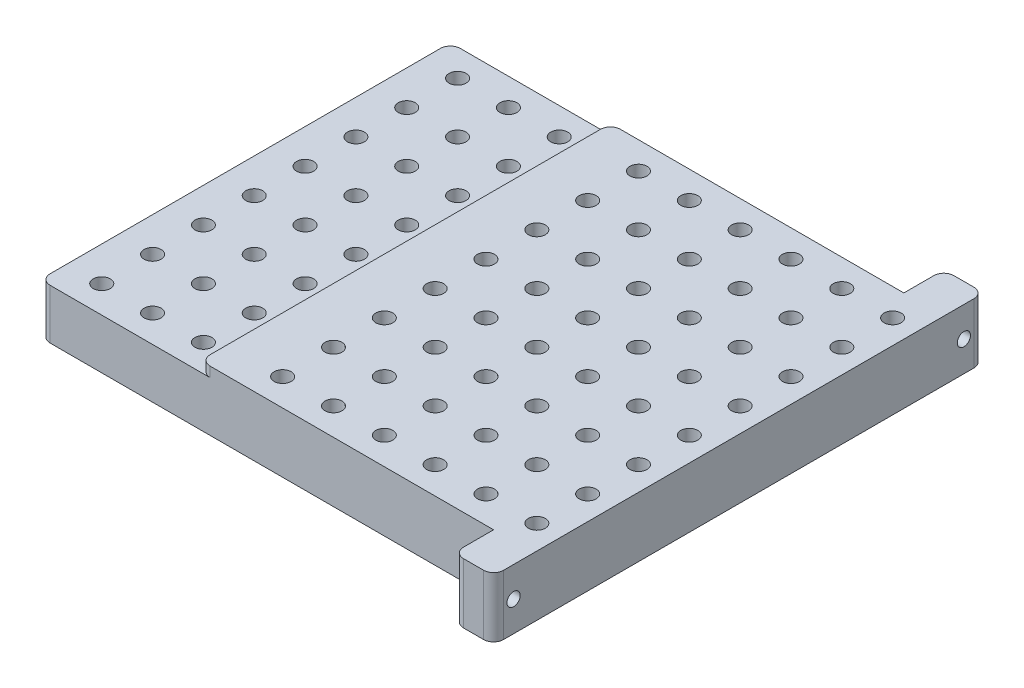
SolidWorks part; units mm, degrees
ref_plane "Front Plane" through (0, 0, 0) normal (0, 0, 1) x (1, 0, 0)
ref_plane "Top Plane" through (0, 0, 0) normal (0, 1, 0) x (1, 0, 0)
ref_plane "Right Plane" through (0, 0, 0) normal (1, 0, 0) x (0, 0, -1)
sketch "Sketch1" plane through (0, 0, 0) normal (0, 0, 1) x (1, 0, 0)
  line L0 (-80, 0) -> (0, 0)
  line L1 (0, 0) -> (0, 5)
  line L2 (0, 5) -> (166.6, 5)
  line L3 (166.6, 5) -> (166.6, -25)
  line L4 (166.6, -25) -> (-80, -25)
  line L5 (-80, -25) -> (-80, 0)
  dimension "D1" = 5
  dimension "D2" = 80
  dimension "D3" = 166.6
  dimension "D4" = 25
extrude "Boss-Extrude1" add sketch "Sketch1" along normal blind 205
sketch "Sketch2" plane through (0, 5, 0) normal (0, 1, 0) x (1, 0, 0)
  line L0 (0, -205) -> (0, 0) construction
  line L2 (166.6, 0) -> (0, 0) construction
  line L4 (166.6, -205) -> (0, -205) construction
  line L7 (-80, -39) -> (166.6, -39) construction
  line L8 (-80, -205) -> (-80, 0) construction
  line L9 (166.6, -205) -> (166.6, 0) construction
  line L11 (-80, -89.8) -> (166.6, -89.8) construction
  line L13 (-80, -140.6) -> (166.6, -140.6) construction
  line L15 (-80, -191.4) -> (166.6, -191.4) construction
  line L17 (-62.8, 0) -> (-62.8, -205) construction
  line L18 (0, 0) -> (-80, 0) construction
  line L19 (0, -205) -> (-80, -205) construction
  line L21 (-12, 0) -> (-12, -205) construction
  line L23 (53, 0) -> (53, -205) construction
  line L25 (103.8, 0) -> (103.8, -205) construction
  line L27 (154.6, 0) -> (154.6, -205) construction
  point P0 (-12, -13.6)
  point P5 (-62.8, -13.6)
  point P8 (-113.6, -13.6)
  point P9 (-62.8, -64.4)
  point P10 (-113.6, -64.4)
  point P11 (-62.8, -115.2)
  point P12 (-113.6, -115.2)
  point P13 (-62.8, -166)
  point P14 (-113.6, -166)
  point P15 (-12, -64.4)
  point P16 (-12, -115.2)
  point P17 (-12, -166)
  point P46 (53, -13.6)
  point P57 (103.8, -13.6)
  point P58 (154.6, -13.6)
  point P59 (103.8, -64.4)
  point P60 (154.6, -64.4)
  point P61 (103.8, -115.2)
  point P62 (154.6, -115.2)
  point P63 (103.8, -166)
  point P64 (154.6, -166)
  point P65 (53, -64.4)
  point P66 (53, -115.2)
  point P67 (53, -166)
  point P126 (-62.8, -39)
  point P128 (-12, -39)
  point P130 (53, -39)
  point P132 (103.8, -39)
  point P134 (154.6, -39)
  point P136 (154.6, -89.8)
  point P138 (103.8, -89.8)
  point P140 (53, -89.8)
  point P142 (-12, -89.8)
  point P144 (-62.8, -89.8)
  point P146 (-62.8, -140.6)
  point P148 (-12, -140.6)
  point P150 (53, -140.6)
  point P152 (103.8, -140.6)
  point P154 (154.6, -140.6)
  point P156 (154.6, -191.4)
  point P158 (103.8, -191.4)
  point P160 (53, -191.4)
  point P162 (-12, -191.4)
  point P164 (-62.8, -191.4)
  point P214 (-37.4, -13.6)
  point P215 (-37.4, -64.4)
  point P216 (-37.4, -115.2)
  point P217 (-37.4, -166)
  point P218 (-37.4, -191.4)
  point P225 (-37.4, -39)
  point P226 (-37.4, -89.8)
  point P227 (-37.4, -140.6)
  point P239 (129.2, -13.6)
  point P240 (129.2, -64.4)
  point P241 (129.2, -115.2)
  point P242 (129.2, -166)
  point P243 (129.2, -39)
  point P244 (129.2, -89.8)
  point P245 (129.2, -140.6)
  point P246 (129.2, -191.4)
  point P257 (78.4, -13.6)
  point P258 (78.4, -64.4)
  point P259 (78.4, -115.2)
  point P260 (78.4, -166)
  point P261 (78.4, -39)
  point P262 (78.4, -89.8)
  point P263 (78.4, -140.6)
  point P264 (78.4, -191.4)
  point P265 (27.6, -13.6)
  point P266 (27.6, -64.4)
  point P267 (27.6, -115.2)
  point P268 (27.6, -166)
  point P269 (27.6, -39)
  point P270 (27.6, -89.8)
  point P271 (27.6, -140.6)
  point P272 (27.6, -191.4)
  dimension "D1" = 12
  dimension "D5" = 50.8
  dimension "D6" = 50.8
  dimension "D7" = 65
  dimension "D8" = 0
  dimension "D11" = 50.8
  dimension "D12" = 50.8
  dimension "D2" = 13.6
  dimension "D15" = 25.4
  dimension "D16" = 50.8
  dimension "D17" = 50.8
  dimension "D18" = 50.8
  dimension "D20" = 25.4
  dimension "D22" = 25.4
  dimension "D24" = 25.4
  dimension "D26" = 50.8
  dimension "D3" = 3
  dimension "D4" = 4
  dimension "D9" = 3
  dimension "D10" = 4
  dimension "D19" = 2
  dimension "D21" = 2
  dimension "D23" = 2
  dimension "D25" = 3
hole_wizard "M8 Clearance Hole1" positions "Sketch2" profile "Sketch3" hole size "M8" standard "ISO" end condition through all
sketch "Sketch3" plane through (-12, 5, 13.6) normal (1, 0, 0) x (0, 0, 1)
  line L0 (0, 0) -> (0, 30)
  line L1 (0, 30) -> (4.25, 30)
  line L2 (4.25, 30) -> (4.25, 0)
  line L5 (4.25, 0) -> (0, 0)
  line L11 (0, -6.35) -> (0, 107.95) construction
  dimension "Thru Hole Dia." = 8.5
  dimension "Thru Hole Depth" = 30
sketch "Sketch5" plane through (0, 0, 205) normal (0, 0, 1) x (1, 0, 0)
  line L0 (166.6, 5) -> (0, 5) construction
  line L1 (166.6, -25) -> (146.6, -25)
  line L2 (166.6, -25) -> (166.6, 5)
  line L3 (166.6, 5) -> (146.6, 5)
  line L4 (146.6, -25) -> (146.6, 5)
  dimension "D1" = 20
fillet "Fillet1" radius 5 4 edges at (-80, -12.5, 0) (-80, -12.5, 205) (0, 2.5, 205) (0, 2.5, 0)
extrude "Boss-Extrude2" add sketch "Sketch5" along normal blind 20
ref_plane "Plane1" through (0, 0, 102.5) normal (0, 0, 1) x (1, 0, 0)
sketch "Sketch7" plane through (146.6, 0, 0) normal (-1, 0, 0) x (0, 0, 1)
  line L0 (225, -25) -> (205, 5) construction
  line L1 (225, 5) -> (205, -25) construction
  circle A0 centre (215, -10) radius 3.3
  dimension "D1" = 6.6
extrude "Cut-Extrude1" cut sketch "Sketch7" against normal up to surface (20 mm away) up to face at (166.6, -10, 112.5)
mirror "Mirror1" about plane through (0, 0, 102.5) normal (0, 0, 1) of "Boss-Extrude2", "Cut-Extrude1"
fillet "Fillet2" radius 5 4 edges at (146.6, -10, 225) (166.6, -10, 225) (146.6, -10, -20) (166.6, -10, -20)
equation "\"D17@Sketch2\"= \"D16@Sketch2\""
equation "\"D18@Sketch2\"=\"D17@Sketch2\""
equation "\"D6@Sketch2\"=\"D5@Sketch2\""
equation "\"D16@Sketch2\"=\"D5@Sketch2\""
equation "\"D15@Sketch2\"=\"D20@Sketch2\""
equation "\"D22@Sketch2\"=\"D20@Sketch2\""
equation "\"D12@Sketch2\"=\"D5@Sketch2\""
equation "\"D11@Sketch2\"=\"D5@Sketch2\""
equation "\"D26@Sketch2\"=\"D5@Sketch2\""
equation "\"D24@Sketch2\"=\"D20@Sketch2\""
